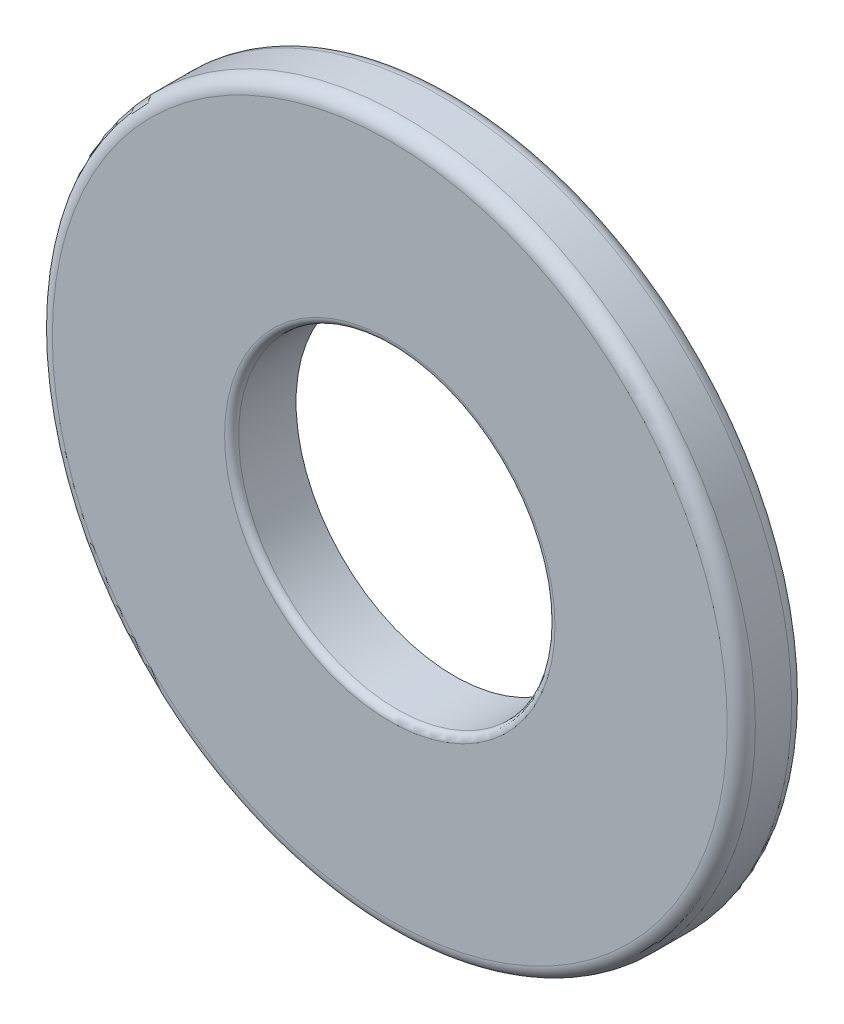
SolidWorks part; units mm, degrees
ref_plane "Front Plane" through (0, 0, 0) normal (0, 0, 1) x (1, 0, 0)
ref_plane "Top Plane" through (0, 0, 0) normal (0, 1, 0) x (1, 0, 0)
ref_plane "Right Plane" through (0, 0, 0) normal (1, 0, 0) x (0, 0, -1)
sketch "Sketch1" plane through (0, 0, 0) normal (0, 0, 1) x (1, 0, 0)
  circle A0 centre (0, 0) radius 3 construction
  circle A1 centre (0, 0) radius 1.35 construction
  point P5 (0, -3)
  dimension "OD" = 6
  dimension "ID" = 2.7
sketch "Sketch2" plane through (0, 0, 0) normal (1, 0, 0) x (0, 0, -1)
  line L0 (0.225, 0) -> (-0.225, 0) construction
  line L1 (-0.275, -3) -> (0.275, -3) construction
  point P0 (-0.275, -3)
  point P3 (0.275, -3)
  point P4 (0, 0)
  point P9 (0, -3)
  point P10 (0.225, -3)
  point P11 (-0.275, -3)
  point P12 (-0.225, -3)
  point P13 (0.275, -3)
  dimension "Thickness Range [Min]" = 0.45
  dimension "Thickness Range [Max]" = 0.55
sketch "Sketch3" plane through (0, 0, 0) normal (0, 0, 1) x (1, 0, 0)
  circle A0 centre (0, 0) radius 1.35 construction
  circle A1 centre (0, 0) radius 3 construction
  circle A2 centre (0, 0) radius 1.35
  circle A3 centre (0, 0) radius 3
extrude "Boss-Extrude1" add sketch "Sketch3" against normal up to vertex (0.275 mm away) and the other way up to vertex (0.275 mm away) up to point (0, -3, -0.275) other way up to point (0, -3, 0.275)
fillet "Fillet1" radius 0.12 2 edges at (3, 0, -0.275) (3, 0, 0.275)
fillet "Fillet2" radius 0.06 1 edges at (1.35, 0, 0.275)
equation "\"D1@Fillet1\"=\"OD@Sketch1\"*.02"
equation "\"D1@Fillet2\"=\"OD@Sketch1\"*.01"
